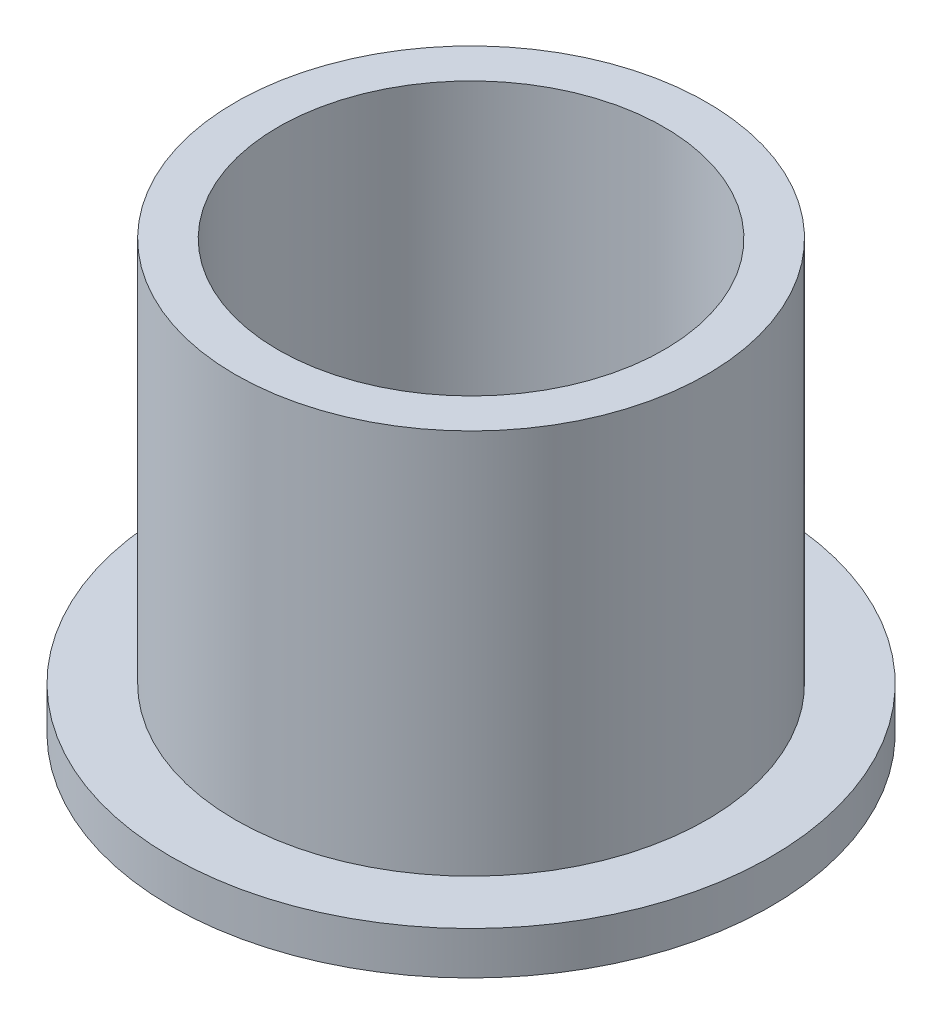
SolidWorks part; units mm, degrees
material "Manganese Bronze"
ref_plane "Front" through (0, 0, 0) normal (0, 0, 1) x (1, 0, 0)
ref_plane "Top" through (0, 0, 0) normal (0, 1, 0) x (1, 0, 0)
ref_plane "Right" through (0, 0, 0) normal (1, 0, 0) x (0, 0, -1)
sketch "Sketch1" plane through (0, 0, 0) normal (0, 1, 0) x (1, 0, 0)
  circle A0 centre (0, 0) radius 14.3002
  circle A1 centre (0, 0) radius 17.4752
  circle A2 centre (0, 0) radius 22.225
  dimension "ID" = 28.6004
  dimension "OD" = 34.9504
  dimension "FlangeOD" = 44.45
sketch "Sketch2" plane through (0, 0, 0) normal (0, 1, 0) x (1, 0, 0)
  circle A0 centre (0, 0) radius 14.3002 construction
  circle A1 centre (0, 0) radius 17.4752 construction
  circle A2 centre (0, 0) radius 14.3002
  circle A3 centre (0, 0) radius 17.4752
extrude "Boss-Extrude1" add sketch "Sketch2" along normal blind 31.75
sketch "Sketch3" plane through (0, 0, 0) normal (0, 1, 0) x (1, 0, 0)
  circle A0 centre (0, 0) radius 22.225 construction
  circle A1 centre (0, 0) radius 17.4752 construction
  circle A2 centre (0, 0) radius 22.225
  circle A3 centre (0, 0) radius 17.4752
extrude "Boss-Extrude2" add sketch "Sketch3" along normal blind 3.175
